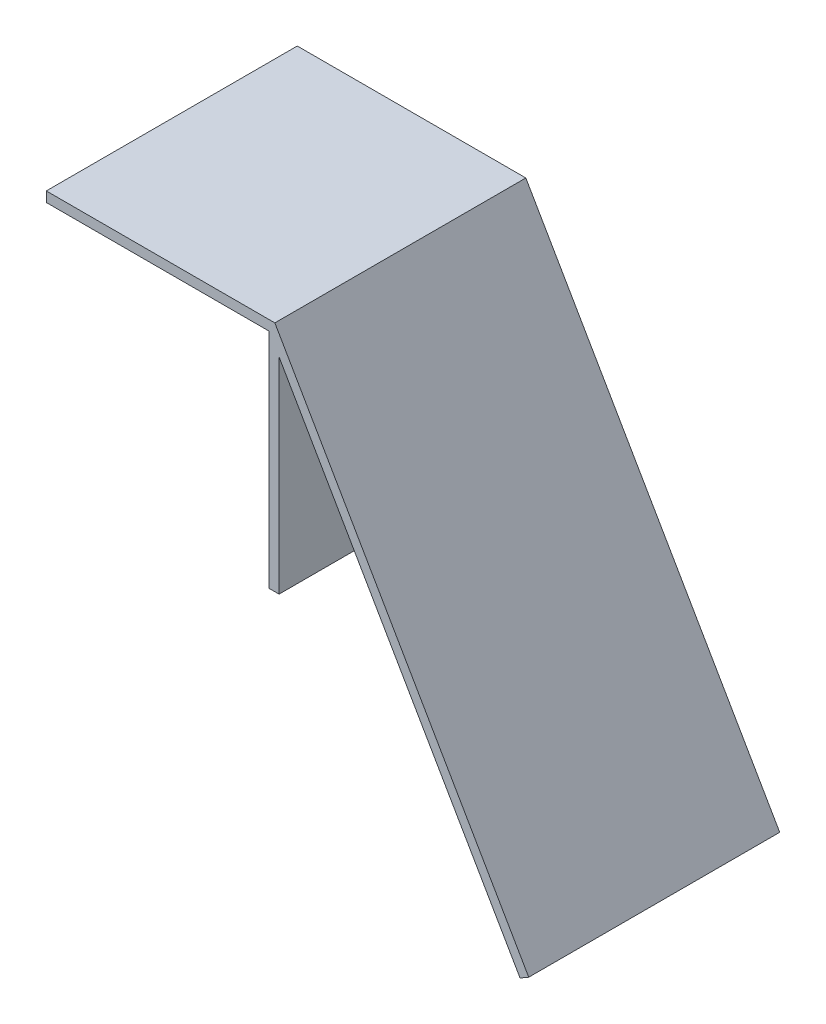
SolidWorks part; units mm, degrees
ref_plane "Front Plane" through (0, 0, 0) normal (0, 0, 1) x (1, 0, 0)
ref_plane "Top Plane" through (0, 0, 0) normal (0, 1, 0) x (1, 0, 0)
ref_plane "Right Plane" through (0, 0, 0) normal (1, 0, 0) x (0, 0, -1)
sketch "Sketch1" plane through (0, 0, 0) normal (0, 0, 1) x (1, 0, 0)
  line L0 (0, 0) -> (22.7664, 0)
  line L1 (22.7664, 0) -> (48.0551, -43.8013)
  line L2 (0, 0) -> (0, -1)
  line L3 (0, -1) -> (22.189, -1)
  line L4 (48.0551, -43.8013) -> (47.189, -44.3013)
  line L5 (47.189, -44.3013) -> (23.189, -2.7321)
  line L8 (22.189, -1) -> (22.189, -23.189)
  line L9 (22.189, -23.189) -> (23.189, -23.189)
  line L10 (23.189, -2.7321) -> (23.189, -23.189)
  dimension "D1" = 1
  dimension "D2" = 1
  dimension "D3" = 60
  dimension "D4" = 50
  dimension "D5" = 22.7664
extrude "Boss-Extrude1" add sketch "Sketch1" along normal blind 25
